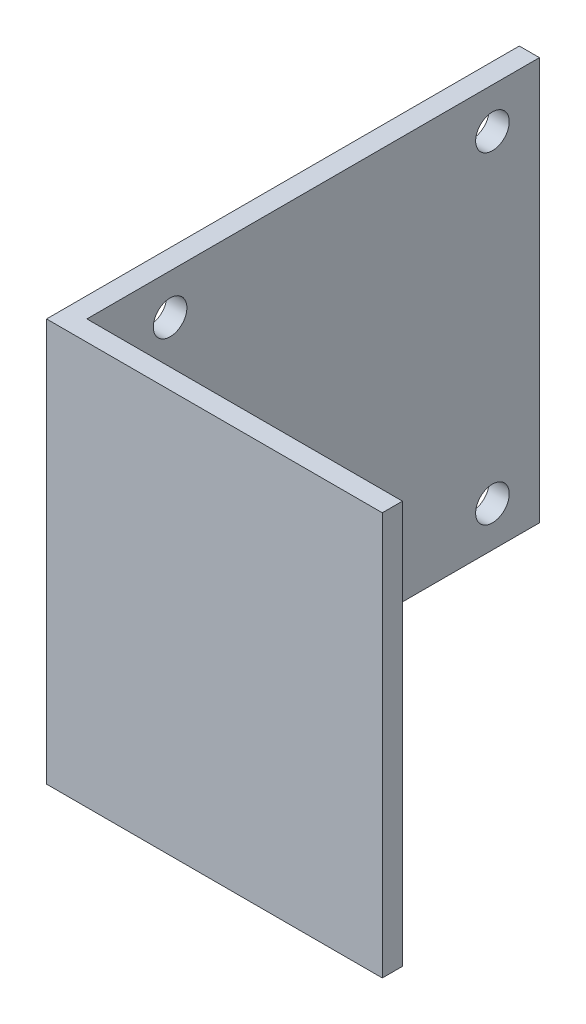
SolidWorks part; units mm, degrees
ref_plane "Front Plane" through (0, 0, 0) normal (0, 0, 1) x (1, 0, 0)
ref_plane "Top Plane" through (0, 0, 0) normal (0, 1, 0) x (1, 0, 0)
ref_plane "Right Plane" through (0, 0, 0) normal (1, 0, 0) x (0, 0, -1)
sketch "Sketch1" plane through (0, 0, 0) normal (0, 1, 0) x (1, 0, 0)
  line L0 (0, 0) -> (0, 70.4)
  line L1 (0, 70.4) -> (3, 70.4)
  line L2 (3, 70.4) -> (3, 3)
  line L3 (3, 3) -> (50, 3)
  line L4 (50, 3) -> (50, 0)
  line L5 (50, 0) -> (0, 0)
  dimension "D1" = 70.4
  dimension "D2" = 3
  dimension "D3" = 3
  dimension "D4" = 50
extrude "Boss-Extrude1" add sketch "Sketch1" along normal blind 60
sketch "Sketch2" plane through (0, 0, 0) normal (-1, 0, 0) x (0, 0, 1)
  line L0 (-70.4, 30) -> (0, 30) construction
  line L1 (-70.4, 60) -> (-70.4, 0) construction
  line L2 (0, 60) -> (0, 0) construction
  circle A0 centre (-63.4, 6) radius 2.5
  circle A1 centre (-15.4, 6) radius 2.5
  circle A2 centre (-15.4, 54) radius 2.5
  circle A3 centre (-63.4, 54) radius 2.5
  dimension "D1" = 5
  dimension "D2" = 5
  dimension "D3" = 48
  dimension "D4" = 48
  dimension "D5" = 7
extrude "Cut-Extrude1" cut sketch "Sketch2" against normal through all
